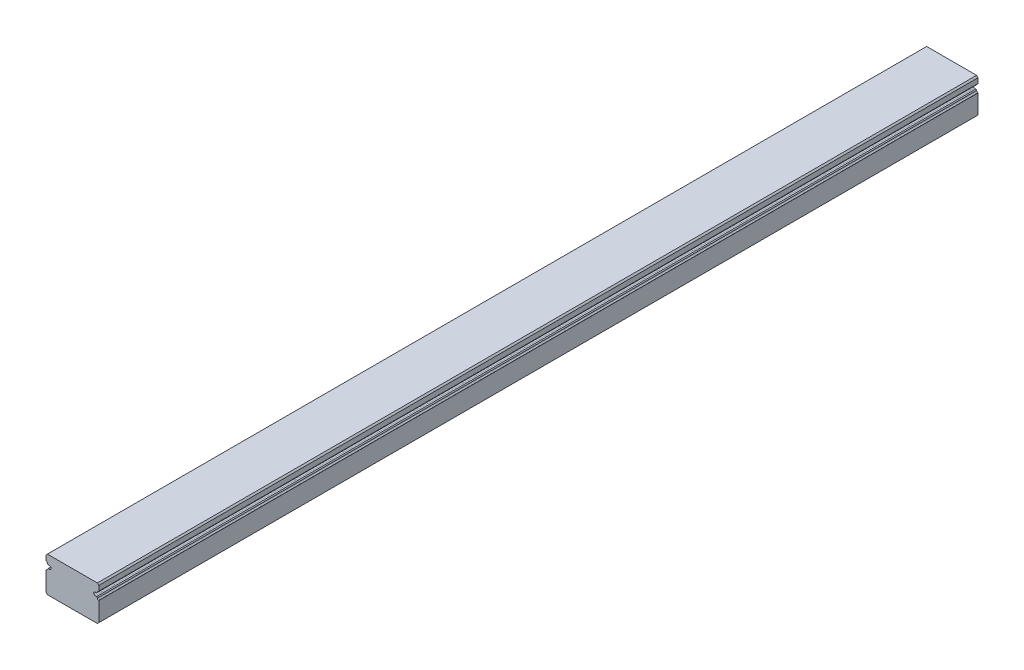
SolidWorks part; units mm, degrees
material "Простая углеродистая сталь"
ref_plane "Спереди" through (0, 0, 0) normal (0, 0, 1) x (1, 0, 0)
ref_plane "Сверху" through (0, 0, 0) normal (0, 1, 0) x (1, 0, 0)
ref_plane "Справа" through (0, 0, 0) normal (1, 0, 0) x (0, 0, -1)
sketch "Model" plane through (0, 0, 0) normal (0, 0, 1) x (1, 0, 0)
  line L0 (-7.1, -5) -> (7.1, -5)
  line L1 (7.1, -5) -> (7.5, -4.6)
  line L2 (7.5, -4.6) -> (7.5, 0.85)
  line L3 (7.5, 0.85) -> (7.4639, 0.8921)
  line L4 (7.1196, 1.2938) -> (6.9, 1.55)
  line L5 (6.9, 1.55) -> (6.5, 1.55)
  line L6 (6.5, 2.45) -> (6.9, 2.45)
  line L7 (6.9, 2.45) -> (7.1196, 2.7062)
  line L8 (7.4639, 3.1079) -> (7.5, 3.15)
  line L9 (7.5, 3.15) -> (7.5, 4.6)
  line L10 (7.5, 4.6) -> (7.1, 5)
  line L11 (7.1, 5) -> (-7.1, 5)
  line L12 (-7.1, 5) -> (-7.5, 4.6)
  line L13 (-7.5, 4.6) -> (-7.5, 3.15)
  line L14 (-7.5, 3.15) -> (-7.4639, 3.1079)
  line L15 (-7.1196, 2.7062) -> (-6.9, 2.45)
  line L16 (-6.9, 2.45) -> (-6.5, 2.45)
  line L17 (-6.5, 1.55) -> (-6.9, 1.55)
  line L18 (-6.9, 1.55) -> (-7.1196, 1.2938)
  line L19 (-7.4639, 0.8921) -> (-7.5, 0.85)
  line L20 (-7.5, 0.85) -> (-7.5, -4.6)
  line L21 (-7.5, -4.6) -> (-7.1, -5)
  arc A1 (7.1196, 1.2938) -> (7.4639, 0.8921) centre (7.5195, 1.2882) ccw
  arc A2 (6.5, 2.45) -> (6.5, 1.55) centre (6.5, 2) ccw
  arc A3 (7.4639, 3.1079) -> (7.1196, 2.7062) centre (7.5195, 2.7118) ccw
  arc A4 (-7.1196, 2.7062) -> (-7.4639, 3.1079) centre (-7.5195, 2.7118) ccw
  arc A5 (-6.5, 1.55) -> (-6.5, 2.45) centre (-6.5, 2) ccw
  arc A6 (-7.4639, 0.8921) -> (-7.1196, 1.2938) centre (-7.5195, 1.2882) ccw
extrude "База" add sketch "Model" along normal mid plane 250
